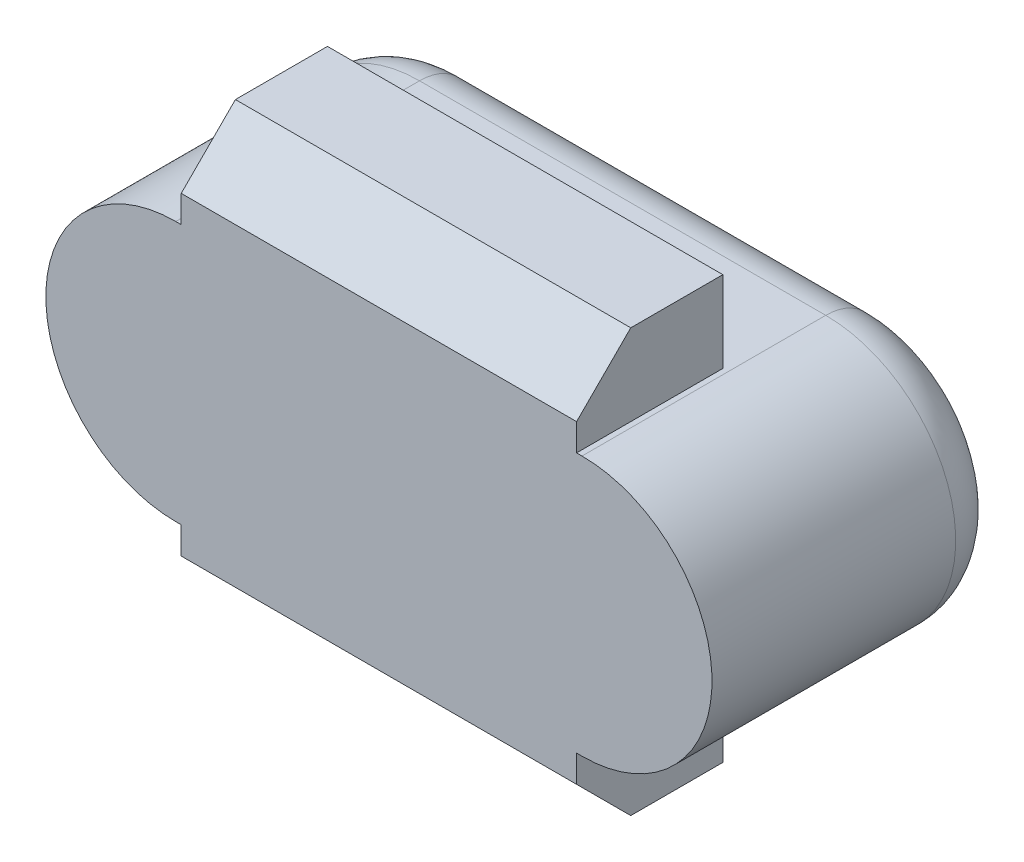
SolidWorks part; units mm, degrees
ref_plane "Спереди" through (0, 0, 0) normal (0, 0, 1) x (1, 0, 0)
ref_plane "Сверху" through (0, 0, 0) normal (0, 1, 0) x (1, 0, 0)
ref_plane "Справа" through (0, 0, 0) normal (1, 0, 0) x (0, 0, -1)
sketch "Эскиз1" plane through (0, 0, 0) normal (0, 0, 1) x (1, 0, 0)
  line L0 (0, 0) -> (7.5, 0) construction
  line L1 (0, 2.4) -> (7.5, 2.4)
  line L2 (0, -2.4) -> (7.5, -2.4)
  line L3 (0, 2.4) -> (0, -2.4) construction
  line L4 (-2.4, 0) -> (9.9, 0) construction
  arc A0 (0, 2.4) -> (0, -2.4) centre (0, 0) ccw
  arc A1 (7.5, -2.4) -> (7.5, 2.4) centre (7.5, 0) ccw
  point P3 (3.75, 0)
  dimension "D1" = 4.8
  dimension "D2" = 12.3
extrude "Бобышка-Вытянуть1" add sketch "Эскиз1" along normal blind 5.5
sketch "Эскиз2" plane through (0, 0, 5.5) normal (0, 0, 1) x (1, 0, 0)
  line L0 (0.1, 3.9) -> (0.1, -3.9)
  line L1 (7.5, 2.4) -> (0, 2.4) construction
  line L2 (0, -2.4) -> (7.5, -2.4) construction
  line L3 (7.4, 3.9) -> (7.4, -3.9)
  line L4 (0.1, 3.9) -> (7.4, 3.9)
  line L5 (0.1, -3.9) -> (7.4, -3.9)
  line L6 (0, 2.4) -> (0, -2.4) construction
  line L7 (7.5, 2.4) -> (7.5, -2.4) construction
  arc A0 (0, 2.4) -> (0, -2.4) centre (0, 0) ccw construction
  dimension "D1" = 1.5
  dimension "D2" = 1.5
  dimension "D3" = 0.1
  dimension "D4" = 0.1
extrude "Бобышка-Вытянуть2" add sketch "Эскиз2" against normal blind 2.7
fillet "Скругление1" radius 1 4 edges at (9.9, 0, 0) (3.75, -2.4, 0) (-2.4, 0, 0) (3.75, 2.4, 0)
chamfer "Фаска1" distance 1 angle 45 2 edges at (3.75, -3.9, 5.5) (3.75, 3.9, 5.5)
